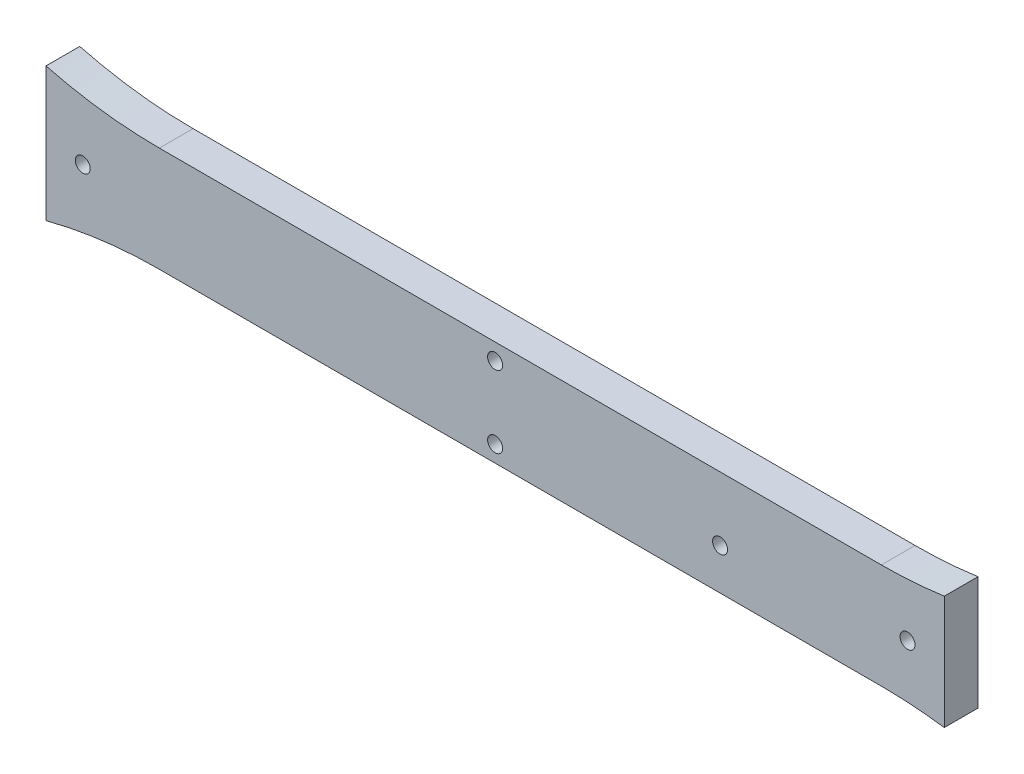
SolidWorks part; units mm, degrees
ref_plane "정면" through (0, 0, 0) normal (0, 0, 1) x (1, 0, 0)
ref_plane "윗면" through (0, 0, 0) normal (0, 1, 0) x (1, 0, 0)
ref_plane "우측면" through (0, 0, 0) normal (1, 0, 0) x (0, 0, -1)
sketch "스케치1" plane through (0, 0, 0) normal (0, 0, 1) x (1, 0, 0)
  line L1 (-59.9, 7) -> (59.9, 7)
  line L2 (-59.9, 7) -> (-59.9, -7)
  line L3 (-59.9, -7) -> (59.9, -7)
  line L4 (59.9, 7) -> (59.9, -7)
  line L5 (-59.9, 7) -> (59.9, -7) construction
  line L6 (-59.9, -7) -> (59.9, 7) construction
  circle A0 centre (0, -4.8) radius 1
  circle A1 centre (0, 4.8) radius 1
  circle A2 centre (-55, 0) radius 1
  circle A3 centre (55, 0) radius 1
  point P0 (0, 0)
  dimension "D3" = 2
  dimension "D4" = 2
  dimension "D7" = 2
  dimension "D8" = 2
  dimension "D1" = 119.8
  dimension "D2" = 14
  dimension "D5" = 2.2
  dimension "D6" = 2.2
  dimension "D9" = 4.9
  dimension "D10" = 4.9
extrude "보스-돌출1" add sketch "스케치1" along normal blind 4.5 contours L4 L1 L2 L3 A3 A2 A1 A0
sketch "스케치2" plane through (0, 0, 0) normal (0, 0, -1) x (-1, 0, 0)
  line L0 (59.9, -7) -> (-59.9, -7) construction
  circle A0 centre (-30, -1.5) radius 1
  dimension "D1" = 2
  dimension "D2" = 25
  dimension "D3" = 5.5
extrude "컷-돌출1" cut sketch "스케치2" against normal through all contours A0
sketch "스케치3" plane through (0, 0, 0) normal (0, 0, -1) x (-1, 0, 0)
  line L0 (-66.5147, 7) -> (63.4566, 7)
  line L1 (59.9, 7) -> (59.9, -7) construction
  line L2 (-59.9, 7) -> (-59.9, -7) construction
  line L3 (-66.5147, -7) -> (63.4566, -7)
  line L8 (-59.9, 7) -> (-59.9, -7)
  line L9 (59.9, 7) -> (59.9, -7)
  circle A0 centre (-75, 0) radius 11
  circle A1 centre (75, 0) radius 13.5
  point P10 (0, 0)
  circle M2 centre (-30, -1.5) radius 1
  line M7 (-59.9, 7) -> (-59.9, -7)
  line M9 (59.9, -7) -> (59.9, 7)
  dimension "D2" = 22
  dimension "D3" = 27
  dimension "D1" = 15.1
  dimension "D4" = 15.1
sketch "스케치4" plane through (0, 0, 0) normal (0, 0, -1) x (-1, 0, 0)
  line L1 (-59.9, -17.5892) -> (-95.7367, -17.5892)
  line L2 (-59.9, -17.5892) -> (-59.9, 19.2111)
  line L3 (-59.9, 19.2111) -> (-95.7367, 19.2111)
  line L4 (-95.7367, -17.5892) -> (-95.7367, 19.2111)
  line L5 (59.9, -24.3897) -> (96.6925, -24.3897)
  line L6 (59.9, -24.3897) -> (59.9, 21.014)
  line L7 (59.9, 21.014) -> (96.6925, 21.014)
  line L8 (96.6925, -24.3897) -> (96.6925, 21.014)
extrude "보스-돌출3" add sketch "스케치3" against normal up to surface (4.5 mm away) from surface at 0 contours A0 | A0 L3 L0 M7 | A1 L0 L3 M9 | A1 M2
fillet "필렛2" radius 60 4 edges at (-63.4566, 7, 2.25) (-63.4566, -7, 2.25) (66.5147, -7, 2.25) (66.5147, 7, 2.25)
extrude "컷-돌출3" cut sketch "스케치4" against normal blind 10
